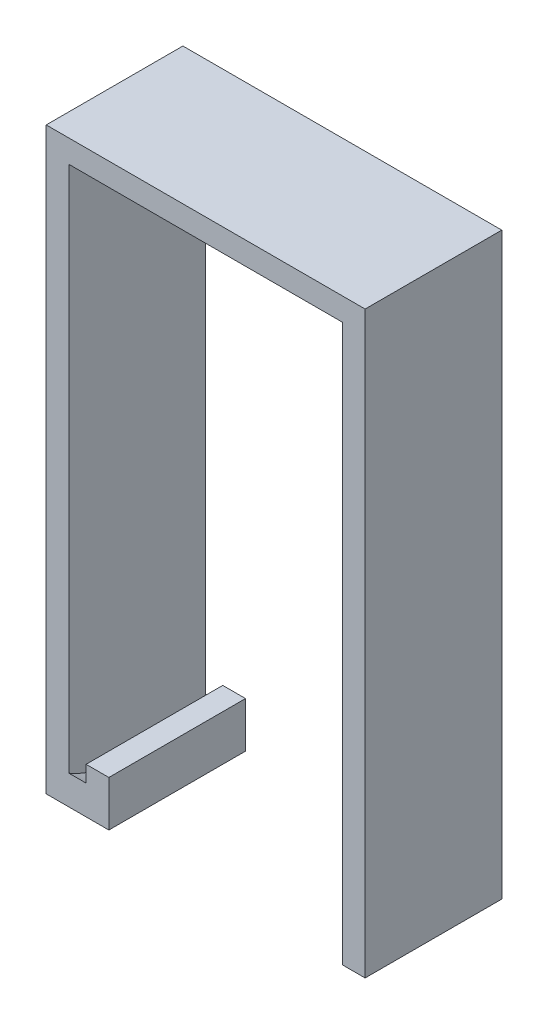
SolidWorks part; units mm, degrees
ref_plane "Plano frontal" through (0, 0, 0) normal (0, 0, 1) x (1, 0, 0)
ref_plane "Plano superior" through (0, 0, 0) normal (0, 1, 0) x (1, 0, 0)
ref_plane "Plano direito" through (0, 0, 0) normal (1, 0, 0) x (0, 0, -1)
sketch "Sketch1" plane through (0, 0, 0) normal (0, 1, 0) x (1, 0, 0)
  line L1 (-12, 6) -> (12, 6)
  line L2 (-12, 6) -> (-12, -6)
  line L3 (-12, -6) -> (12, -6)
  line L4 (12, 6) -> (12, -6)
  point P4 (0, 6)
  point P6 (-12, 0)
  dimension "D1" = 24
  dimension "D2" = 12
extrude "Boss-Extrude1" add sketch "Sketch1" along normal mid plane 2
sketch "Sketch2" plane through (-12, 0, 0) normal (-1, 0, 0) x (0, 0, 1)
  line L0 (6, 1) -> (6, -1) construction
  line L1 (-6, 1) -> (6, 1)
  line L2 (-6, 1) -> (-6, -49.87)
  line L3 (-6, -49.87) -> (6, -49.87)
  line L4 (6, 1) -> (6, -49.87)
  dimension "D1" = 50.87
extrude "Boss-Extrude2" add sketch "Sketch2" along normal blind 2
mirror "Mirror1" about plane through (0, 0, 0) normal (1, 0, 0) of "Boss-Extrude2"
sketch "Sketch4" plane through (-12, 0, 0) normal (1, 0, 0) x (0, 0, -1)
  line L2 (6, -49.87) -> (-6, -49.87) construction
  line L3 (-6, -47.3) -> (-6, -49.87)
  line L7 (6, -49.87) -> (6, -1)
  line L8 (6, -1) -> (-6, -1)
  line L9 (-6, -1) -> (-6, -49.87)
  line L10 (-6, -49.87) -> (6, -49.87)
  line L11 (6, -49.87) -> (6, -47.3)
  line L14 (-6, -49.87) -> (6, -49.87)
  arc A0 (-6, -47.3) -> (6, -47.3) centre (0, -36.62) ccw
  arc A1 (6, -47.3) -> (-6, -47.3) centre (0, -36.62) ccw construction
  point P4 (-0.9019, -36.87)
  point P5 (0, 0)
  point P9 (-5.7502, -47.4026)
  dimension "D1" = 24.5
  dimension "D2" = 1
  dimension "D3" = 0
extrude "Boss-Extrude3" add sketch "Sketch4" along normal blind 1.5
sketch "Sketch5" plane through (-10.5, 0, 0) normal (1, 0, 0) x (0, 0, -1)
  line L0 (6, -1) -> (6, -47.3) construction
  line L1 (-6, -49.87) -> (6, -49.87)
  line L2 (-6, -49.87) -> (-6, -45.87)
  line L3 (-6, -45.87) -> (6, -45.87)
  line L4 (6, -49.87) -> (6, -45.87)
  dimension "D1" = 4
extrude "Boss-Extrude4" add sketch "Sketch5" along normal blind 2
